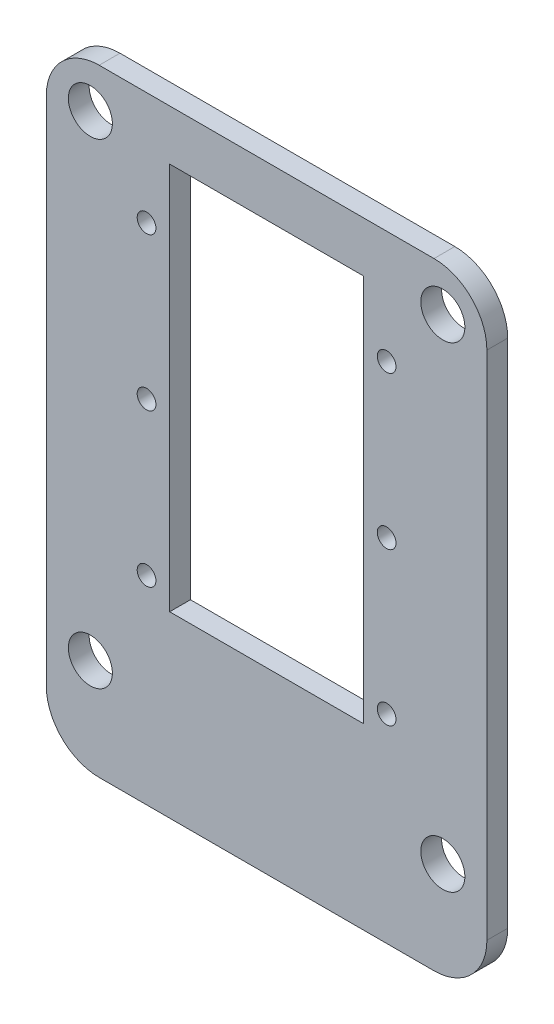
SolidWorks part; units mm, degrees
ref_plane "Front Plane" through (0, 0, 0) normal (0, 0, 1) x (1, 0, 0)
ref_plane "Top Plane" through (0, 0, 0) normal (0, 1, 0) x (1, 0, 0)
ref_plane "Right Plane" through (0, 0, 0) normal (1, 0, 0) x (0, 0, -1)
sketch "Sketch1" plane through (0, 0, 0) normal (0, 0, 1) x (1, 0, 0)
  line L0 (-19.6989, 23.2988) -> (-14.85, 29.7515)
  line L1 (-13.2512, 30.55) -> (13.2512, 30.55)
  line L2 (-20.1, 22.0973) -> (-20.1, -22.0973)
  line L3 (-13.2512, -30.55) -> (13.2512, -30.55)
  line L4 (20.1, 22.0973) -> (20.1, -22.0973)
  line L5 (-20.1, 30.55) -> (20.1, -30.55) construction
  line L6 (-20.1, -30.55) -> (20.1, 30.55) construction
  line L7 (14.85, 29.7515) -> (19.6989, 23.2988)
  line L8 (19.6989, -23.2988) -> (14.85, -29.7515)
  line L9 (-14.85, -29.7515) -> (-19.6989, -23.2988)
  arc A0 (-19.6989, -23.2988) -> (-20.1, -22.0973) centre (-18.1, -22.0973) cw
  arc A1 (-14.85, -29.7515) -> (-13.2512, -30.55) centre (-13.2512, -28.55) ccw
  arc A2 (14.85, -29.7515) -> (13.2512, -30.55) centre (13.2512, -28.55) cw
  arc A3 (19.6989, -23.2988) -> (20.1, -22.0973) centre (18.1, -22.0973) ccw
  arc A4 (19.6989, 23.2988) -> (20.1, 22.0973) centre (18.1, 22.0973) cw
  arc A5 (14.85, 29.7515) -> (13.2512, 30.55) centre (13.2512, 28.55) ccw
  arc A6 (-14.85, 29.7515) -> (-13.2512, 30.55) centre (-13.2512, 28.55) cw
  arc A7 (-19.6989, 23.2988) -> (-20.1, 22.0973) centre (-18.1, 22.0973) ccw
  point P0 (0, 0)
  point P16 (-20.1, -22.765)
  point P19 (-14.25, -30.55)
  point P22 (14.25, -30.55)
  point P25 (20.1, -22.765)
  point P28 (20.1, 22.765)
  point P31 (14.25, 30.55)
  point P34 (-14.25, 30.55)
  point P37 (-20.1, 22.765)
  dimension "D11" = 2
  dimension "D1" = 40.2
  dimension "D2" = 61.1
  dimension "D3" = 5.85
  dimension "D4" = 7.785
  dimension "D5" = 5.85
  dimension "D6" = 7.785
  dimension "D7" = 7.785
  dimension "D8" = 5.85
  dimension "D9" = 5.85
  dimension "D10" = 7.785
extrude "Boss-Extrude1" add sketch "Sketch1" against normal blind 3
sketch "Sketch2" plane through (0, 0, -3) normal (0, 0, -1) x (-1, 0, 0)
  line L0 (14.85, 29.7515) -> (14.85, -29.7515) construction
  line L1 (-14.85, 29.7515) -> (-14.85, -29.7515) construction
  line L2 (19.6989, 23.2988) -> (-19.6989, 23.2988) construction
  line L3 (20.1, -22.0973) -> (-20.1, -22.0973) construction
  line L4 (0, 30.55) -> (0, -30.55) construction
  line L5 (-13.2512, 30.55) -> (13.2512, 30.55) construction
  line L6 (13.2512, -30.55) -> (-13.2512, -30.55) construction
  circle A0 centre (17.3, 21.9488) radius 1.35
  circle A1 centre (17.3, -0.0512) radius 1.35
  circle A2 centre (17.3, -22.0512) radius 1.35
  circle A3 centre (11, -27.75) radius 1.385
  circle A4 centre (-11, -27.75) radius 1.385
  circle A5 centre (-17.3, -22.0512) radius 1.35
  circle A6 centre (-17.3, -0.0512) radius 1.35
  circle A7 centre (-17.3, 21.9488) radius 1.35
  dimension "D1" = 2.7
  dimension "D5" = 2.77
  dimension "D2" = 22
  dimension "D3" = 22
  dimension "D4" = 17.3
  dimension "D6" = 11
  dimension "D7" = 2.8
extrude "Cut-Extrude1" cut sketch "Sketch2" against normal through all
sketch "Sketch3" plane through (0, 0, -3) normal (0, 0, -1) x (-1, 0, 0)
  line L2 (-31.75, 38.2048) -> (31.75, 38.2048)
  line L3 (-31.75, 38.2048) -> (-31.75, -50.6952)
  line L4 (-31.75, -50.6952) -> (31.75, -50.6952)
  line L6 (31.75, 38.2048) -> (31.75, -50.6952)
  line L9 (-19.1605, 23.6188) -> (19.1605, 23.6188)
  line L10 (-19.1605, 23.6188) -> (-19.1605, -23.6188)
  line L11 (-19.1605, -23.6188) -> (19.1605, -23.6188)
  line L12 (19.1605, 23.6188) -> (19.1605, -23.6188)
  circle A0 centre (17.3, 21.9488) radius 1.35 construction
  point P0 (0, 0)
  point P6 (0, 0)
  dimension "D4" = 16.256
  dimension "D1" = 63.5
  dimension "D2" = 88.9
  dimension "D3" = 31.75
extrude "Boss-Extrude2" add sketch "Sketch3" against normal blind 3
sketch "Sketch5" plane through (0, 0, 0) normal (0, 0, 1) x (1, 0, 0)
  line L1 (-13.97, 30.9488) -> (13.97, 30.9488)
  line L2 (-13.97, 30.9488) -> (-13.97, -24.9312)
  line L3 (-13.97, -24.9312) -> (13.97, -24.9312)
  line L4 (13.97, 30.9488) -> (13.97, -24.9312)
  circle A0 centre (17.3, 21.9488) radius 1.35 construction
  dimension "D1" = 27.94
  dimension "D2" = 55.88
  dimension "D3" = 9
extrude "Cut-Extrude3" cut sketch "Sketch5" against normal through all
sketch "Sketch6" plane through (0, 0, -3) normal (0, 0, -1) x (-1, 0, 0)
  line L0 (-13.97, 30.9488) -> (13.97, 30.9488) construction
  line L1 (31.75, 38.2048) -> (-31.75, 38.2048) construction
  circle A0 centre (25.4, 31.8548) radius 3.175
  circle A1 centre (-25.4, 31.8548) radius 3.175
  circle A2 centre (-25.4, -36.7252) radius 3.175
  circle A3 centre (25.4, -36.7252) radius 3.175
  point P4 (0, 30.9488)
  dimension "D1" = 25.4
  dimension "D2" = 6.35
  dimension "D5" = 50.8
  dimension "D3" = 2
  dimension "D4" = 2
extrude "Cut-Extrude4" cut sketch "Sketch6" against normal through all
fillet "Fillet2" radius 7.62 4 edges at (-31.75, -50.6952, -1.5) (31.75, -50.6952, -1.5) (-31.75, 38.2048, -1.5) (31.75, 38.2048, -1.5)
